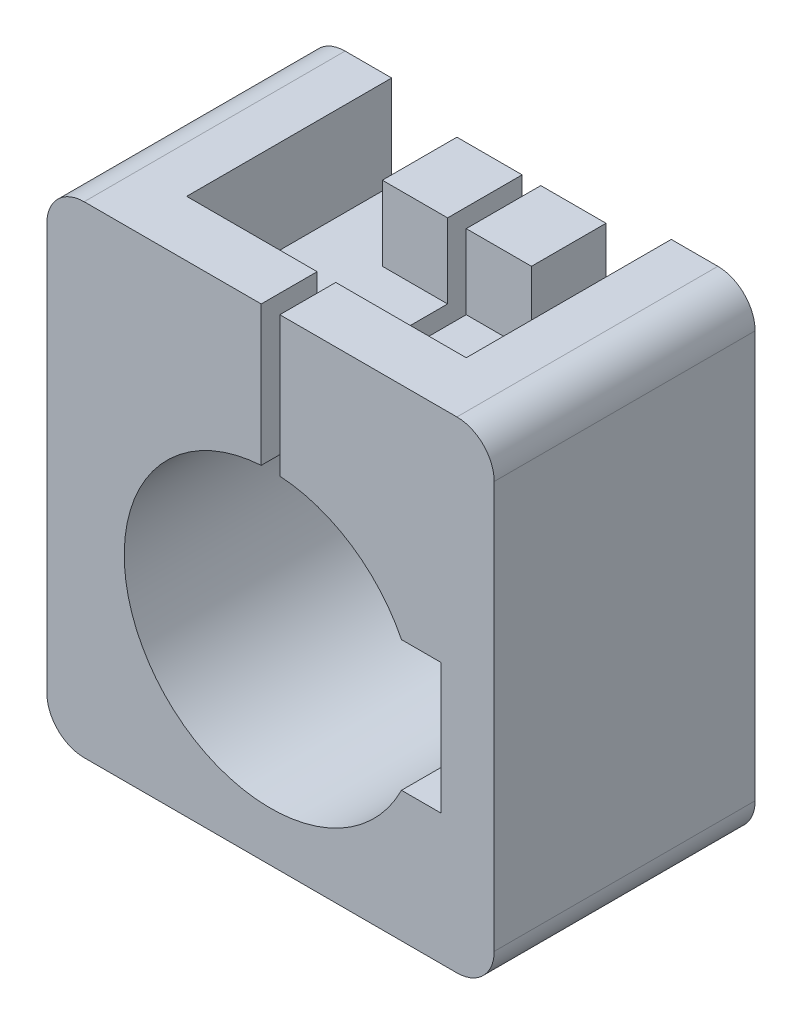
SolidWorks part; units mm, degrees
ref_plane "Alzado" through (0, 0, 0) normal (0, 0, 1) x (1, 0, 0)
ref_plane "Planta" through (0, 0, 0) normal (0, 1, 0) x (1, 0, 0)
ref_plane "Vista lateral" through (0, 0, 0) normal (1, 0, 0) x (0, 0, -1)
sketch "Croquis1" plane through (0, 0, 0) normal (0, 0, 1) x (1, 0, 0)
  line L7 (-12, -10.5) -> (12, -10.5)
  line L8 (9.15, 3.5) -> (7.0266, 3.5)
  line L9 (9.15, 3.5) -> (9.15, -3.5)
  line L10 (9.15, -3.5) -> (7.0266, -3.5)
  line L11 (7.0266, 3.5) -> (7.0266, -3.5) construction
  line L12 (-12, -10.5) -> (-12, 10.3341)
  line L13 (-12, 10.3341) -> (-0.5, 10.3341)
  line L14 (12, 10.3341) -> (12, -10.5)
  line L15 (0.5, 10.3341) -> (12, 10.3341)
  line L16 (-0.5, 10.3341) -> (0.5, 10.3341) construction
  line L17 (-0.5, 10.3341) -> (-0.5, 7.8341)
  line L18 (-0.5, 7.8341) -> (0.5, 7.8341) construction
  line L19 (0.5, 10.3341) -> (0.5, 7.8341)
  arc A2 (7.0266, 3.5) -> (0.5, 7.8341) centre (0, 0) ccw
  arc A3 (-0.5, 7.8341) -> (7.0266, -3.5) centre (0, 0) ccw
  point P7 (-7.85, 0)
  point P8 (7.0266, 0)
  point P11 (0, -10.5)
  point P17 (0, 10.3341)
  dimension "D1" = 15.7
  dimension "D2" = 17
  dimension "D3" = 7
  dimension "D4" = 10.5
  dimension "D5" = 24
  dimension "D6" = 2.5
  dimension "D7" = 1
extrude "Saliente-Extruir1" add sketch "Croquis1" along normal mid plane 14
sketch "Croquis2" plane through (0, 0, -7) normal (0, 0, 1) x (1, 0, 0)
  line L0 (0.5, 14.3341) -> (-0.5, 14.3341) construction
  line L1 (0.5, 10.3341) -> (4, 10.3341)
  line L2 (0.5, 10.3341) -> (0.5, 14.3341)
  line L3 (0.5, 14.3341) -> (4, 14.3341)
  line L4 (4, 10.3341) -> (4, 14.3341)
  line L5 (-0.5, 10.3341) -> (-4, 10.3341)
  line L6 (-0.5, 10.3341) -> (-0.5, 14.3341)
  line L7 (-0.5, 14.3341) -> (-4, 14.3341)
  line L8 (-4, 10.3341) -> (-4, 14.3341)
  dimension "D1" = 4
  dimension "D2" = 3.5
extrude "Saliente-Extruir2" add sketch "Croquis2" along normal blind 4
sketch "Croquis3" plane through (0, 0, 7) normal (0, 0, -1) x (-1, 0, 0)
  line L0 (-12, -10.5) -> (-12, 10.3341) construction
  line L1 (-0.5, 10.3341) -> (-12, 10.3341)
  line L2 (-0.5, 10.3341) -> (-0.5, 15.3341)
  line L3 (-0.5, 15.3341) -> (-12, 15.3341)
  line L4 (-12, 10.3341) -> (-12, 15.3341)
  line L5 (0.5, 10.3341) -> (12, 10.3341)
  line L6 (0.5, 10.3341) -> (0.5, 15.3341)
  line L7 (0.5, 15.3341) -> (12, 15.3341)
  line L8 (12, 10.3341) -> (12, 15.3341)
  line L9 (0.5, 10.3341) -> (-0.5, 10.3341) construction
  line L10 (-0.5, 10.3341) -> (-4, 10.3341) construction
  line L11 (0.5, 10.3341) -> (0.5, 14.3341) construction
  line L12 (-0.5, 14.3341) -> (-0.5, 10.3341) construction
  dimension "D2" = 5
extrude "Saliente-Extruir3" add sketch "Croquis3" along normal blind 3
sketch "Croquis4" plane through (0, 0, 0) normal (0, 0, 1) x (1, 0, 0)
  line L0 (-0.5, 10.3341) -> (-12, 10.3341) construction
  line L1 (-7.5, 10.3341) -> (7.5, 10.3341) construction
  line L2 (-7.5, 10.3341) -> (-7.5, 15.3341) construction
  line L3 (-7.5, 15.3341) -> (7.5, 15.3341) construction
  line L4 (7.5, 10.3341) -> (7.5, 15.3341) construction
  line L5 (-12, 15.3341) -> (-0.5, 15.3341) construction
  line L7 (-12, 15.3341) -> (-7.5, 15.3341)
  line L8 (-12, 15.3341) -> (-12, 10.3341)
  line L9 (-12, 10.3341) -> (-7.5, 10.3341)
  line L10 (-7.5, 15.3341) -> (-7.5, 10.3341)
  line L11 (7.5, 15.3341) -> (12, 15.3341)
  line L12 (7.5, 15.3341) -> (7.5, 10.3341)
  line L13 (7.5, 10.3341) -> (12, 10.3341)
  line L14 (12, 15.3341) -> (12, 10.3341)
  point P6 (0, 15.3341)
  dimension "D1" = 15
extrude "Saliente-Extruir4" add sketch "Croquis4" along normal up to surface and the other way up to surface
fillet "Redondeo3" radius 2 4 edges at (12, -10.5, 0) (-12, -10.5, 0) (12, 15.3341, 0) (-12, 15.3341, 0)
